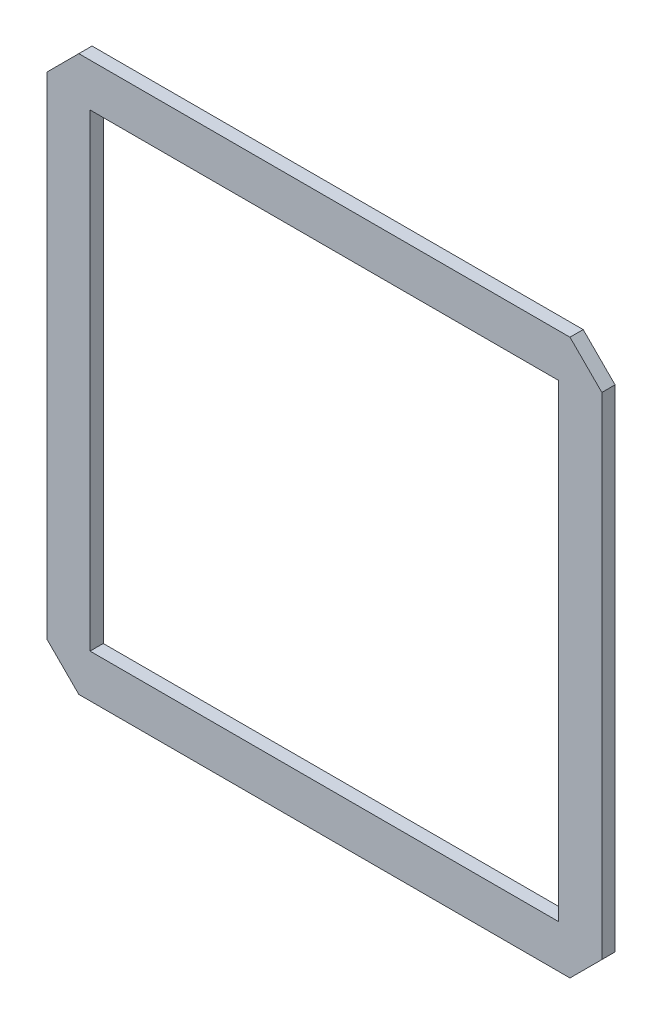
SolidWorks part; units mm, degrees
ref_plane "Front Plane" through (0, 0, 0) normal (0, 0, 1) x (1, 0, 0)
ref_plane "Top Plane" through (0, 0, 0) normal (0, 1, 0) x (1, 0, 0)
ref_plane "Right Plane" through (0, 0, 0) normal (1, 0, 0) x (0, 0, -1)
sketch "Sketch1" plane through (0, 0, 0) normal (0, 0, 1) x (1, 0, 0)
  line L644 (254.2056, 180.7944) -> (254.2056, 287.2056)
  line L645 (254.2056, 287.2056) -> (147.7944, 287.2056)
  line L646 (147.7944, 287.2056) -> (147.7944, 180.7944)
  line L647 (147.7944, 180.7944) -> (254.2056, 180.7944)
  line L648 (256.7574, 297) -> (145.2426, 297)
  line L649 (145.2426, 297) -> (138, 289.7574)
  line L650 (138, 289.7574) -> (138, 178.2426)
  line L651 (138, 178.2426) -> (145.2426, 171)
  line L652 (145.2426, 171) -> (256.7574, 171)
  line L653 (256.7574, 171) -> (264, 178.2426)
  line L654 (264, 178.2426) -> (264, 289.7574)
  line L655 (264, 289.7574) -> (256.7574, 297)
extrude "Boss-Extrude1" add sketch "Sketch1" along normal blind 3
